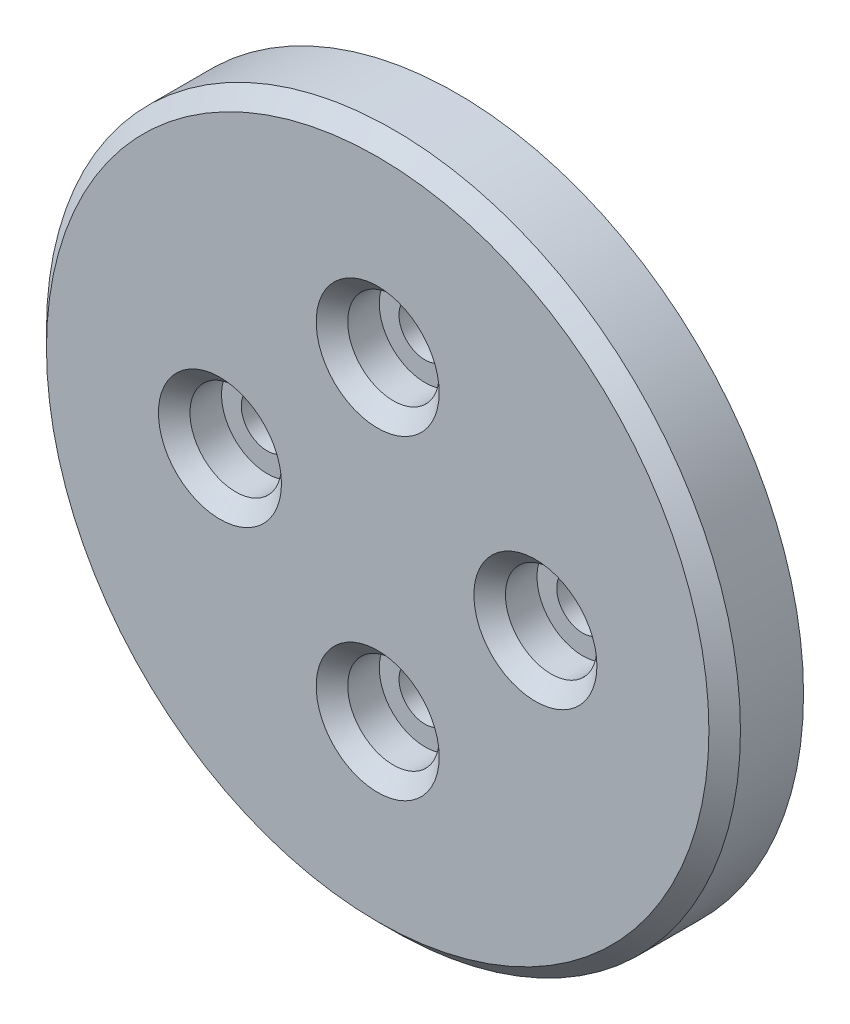
SolidWorks part; units mm, degrees
ref_plane "Ebene vorne" through (0, 0, 0) normal (0, 0, 1) x (1, 0, 0)
ref_plane "Ebene oben" through (0, 0, 0) normal (0, 1, 0) x (1, 0, 0)
ref_plane "Ebene rechts" through (0, 0, 0) normal (1, 0, 0) x (0, 0, -1)
sketch "Skizze1" plane through (0, 0, 0) normal (0, 0, 1) x (1, 0, 0)
  circle A0 centre (0, 0) radius 22
  circle A2 centre (10, 0) radius 1.65
  circle A3 centre (0, -10) radius 1.65
  circle A4 centre (-10, 0) radius 1.65
  circle A5 centre (0, 10) radius 1.65
  point P15 (0, 0)
  dimension "D1" = 44
  dimension "D2" = 10
  dimension "D3" = 4
  dimension "D4" = 3.3
extrude "Aufsatz-Linear austragen1" add sketch "Skizze1" along normal blind 5
sketch "Skizze2" plane through (0, 0, 5) normal (0, 0, 1) x (1, 0, 0)
  circle A0 centre (0, 10) radius 2.9
  circle A1 centre (10, 0) radius 2.9
  circle A2 centre (0, -10) radius 2.9
  circle A3 centre (-10, 0) radius 2.9
  point P12 (0, 0)
  dimension "D1" = 4
  dimension "D2" = 5.8
extrude "Schnitt-Linear austragen1" cut sketch "Skizze2" against normal blind 3
fillet "Verrundung1" radius 1 5 edges at (22, 0, 5) (-7.1, 0, 5) (2.9, -10, 5) (12.9, 0, 5) (2.9, 10, 5) profile chamfer
